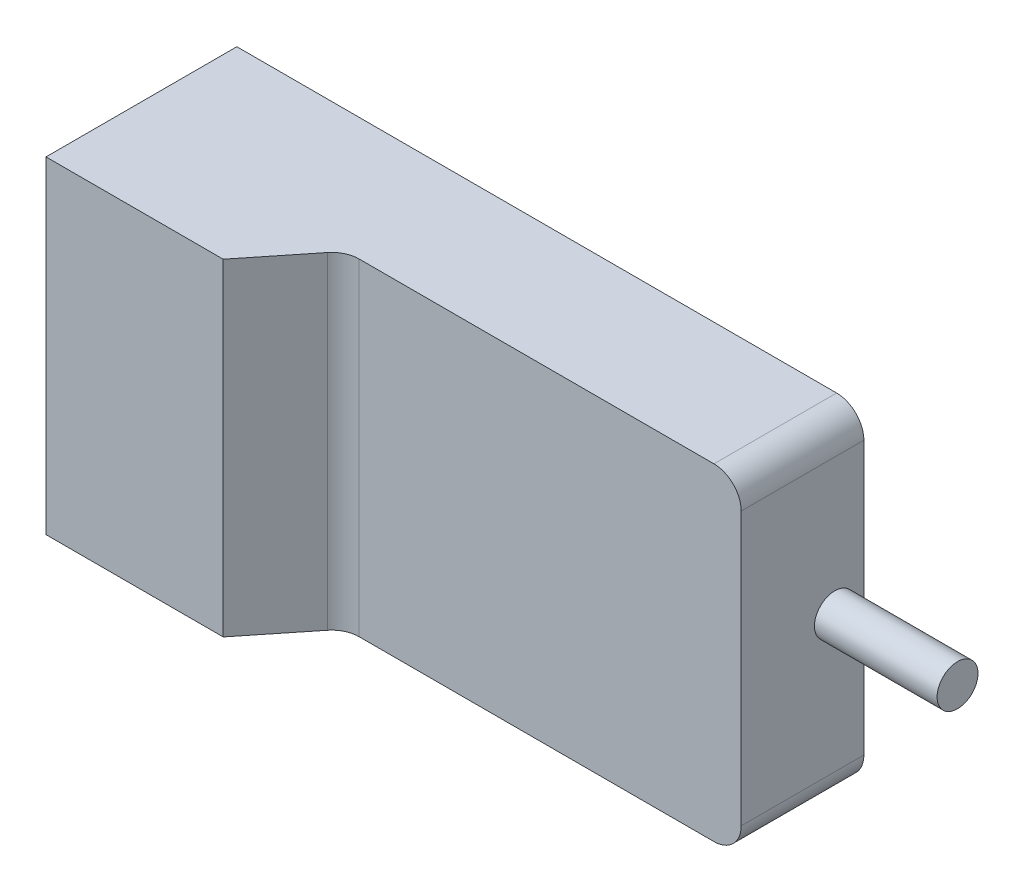
SolidWorks part; units mm, degrees
ref_plane "Спереди" through (0, 0, 0) normal (0, 0, 1) x (1, 0, 0)
ref_plane "Сверху" through (0, 0, 0) normal (0, 1, 0) x (1, 0, 0)
ref_plane "Справа" through (0, 0, 0) normal (1, 0, 0) x (0, 0, -1)
sketch "Эскиз1" plane through (0, 0, 0) normal (0, 0, 1) x (1, 0, 0)
  line L1 (-23, 12) -> (23, 12)
  line L2 (-23, 12) -> (-23, -12)
  line L3 (-23, -12) -> (23, -12)
  line L4 (23, 12) -> (23, -12)
  line L5 (-23, 12) -> (23, -12) construction
  line L6 (-23, -12) -> (23, 12) construction
  point P0 (0, 0)
  dimension "D1" = 46
  dimension "D2" = 24
extrude "Бобышка-Вытянуть1" add sketch "Эскиз1" along normal blind 9
sketch "Эскиз2" plane through (0, 0, 9) normal (0, 0, 1) x (1, 0, 0)
  line L0 (-23, -12) -> (23, -12) construction
  line L1 (-23, 12) -> (-6, 12)
  line L2 (-23, 12) -> (-23, -12)
  line L3 (-23, -12) -> (-6, -12)
  line L4 (-6, 12) -> (-6, -12)
  dimension "D1" = 17
ref_plane "Плоскость1" through (0, 0, 14) normal (0, 0, 1) x (1, 0, 0)
sketch "Эскиз3" plane through (0, 0, 14) normal (0, 0, 1) x (1, 0, 0)
  line L0 (-23, -12) -> (-6, -12) construction
  line L1 (-23, 12) -> (-10, 12)
  line L2 (-23, 12) -> (-23, -12)
  line L3 (-23, -12) -> (-10, -12)
  line L4 (-10, 12) -> (-10, -12)
  dimension "D1" = 13
loft "По сечениям1" add profiles "Эскиз2", "Эскиз3"
sketch "Эскиз4" plane through (23, 0, 0) normal (1, 0, 0) x (0, 0, -1)
  circle A0 centre (-2.1286, 0) radius 1.5
  dimension "D1" = 3
extrude "Бобышка-Вытянуть2" add sketch "Эскиз4" along normal blind 9
fillet "Скругление1" radius 2 3 edges at (23, -12, 4.5) (23, 12, 4.5)
